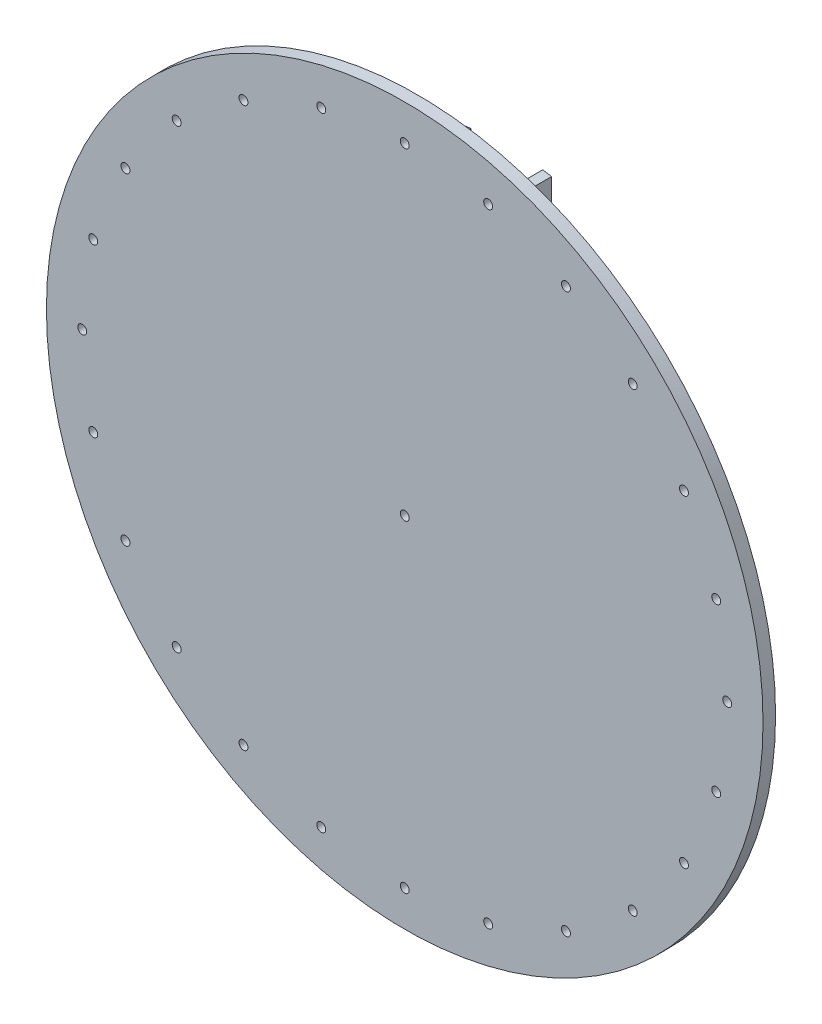
SolidWorks part; units mm, degrees
material "Plain Carbon Steel"
ref_plane "Front Plane" through (0, 0, 0) normal (0, 0, 1) x (1, 0, 0)
ref_plane "Top Plane" through (0, 0, 0) normal (0, 1, 0) x (1, 0, 0)
ref_plane "Right Plane" through (0, 0, 0) normal (1, 0, 0) x (0, 0, -1)
sketch "Sketch2" plane through (0, 0, 0) normal (0, 0, 1) x (1, 0, 0)
  line L0 (0, -23.094) -> (118.7439, -91.6509)
  line L1 (0, 28.8675) -> (142.4038, -53.3494) construction
  line L2 (20, 11.547) -> (138.7439, -57.0098)
  line L3 (-20, 11.547) -> (-20, 148.6607)
  line L4 (0, 23.094) -> (139.9038, -57.6795) construction
  line L5 (20, 11.547) -> (20, 148.6607)
  line L6 (0, -23.094) -> (-118.7439, -91.6509)
  line L7 (-20, -11.547) -> (119.9038, -92.3205) construction
  line L8 (-20, 11.547) -> (-138.7439, -57.0098)
  line L9 (-25, -14.4338) -> (117.4038, -96.6506) construction
  line L10 (-25, -14.4338) -> (-25, 150) construction
  line L11 (-25, 14.4338) -> (-25, 147.902)
  line L12 (0, -28.8675) -> (115.5869, -95.6016)
  line L13 (0, -28.8675) -> (-115.5869, -95.6016)
  line L14 (25, 14.4338) -> (25, 147.902)
  line L15 (-25, 14.4338) -> (-140.5869, -52.3004)
  line L16 (25, 14.4338) -> (140.5869, -52.3004)
  line L17 (-20, -11.547) -> (-20, 150) construction
  line L18 (20, -11.547) -> (20, 150) construction
  line L19 (25, -14.4338) -> (25, 150) construction
  line L20 (20, -11.547) -> (-119.9038, -92.3205) construction
  line L21 (25, -14.4338) -> (-117.4038, -96.6506) construction
  line L22 (0, 28.8675) -> (-142.4038, -53.3494) construction
  line L23 (0, 23.094) -> (-139.9038, -57.6795) construction
  arc A0 (25, 147.902) -> (20, 148.6607) centre (0, 0) ccw
  arc A1 (-140.5869, -52.3004) -> (-138.7439, -57.0098) centre (0, 0) ccw
  arc A2 (115.5869, -95.6016) -> (118.7439, -91.6509) centre (0, 0) ccw
  arc A3 (-118.7439, -91.6509) -> (-115.5869, -95.6016) centre (0, 0) ccw
  arc A4 (138.7439, -57.0098) -> (140.5869, -52.3004) centre (0, 0) ccw
  arc A5 (-20, 148.6607) -> (-25, 147.902) centre (0, 0) ccw
  point P20 (0, 0)
  dimension "D1" = 300
  dimension "D5" = 5
  dimension "D6" = 5
  dimension "D4" = 3
extrude "Boss-Extrude2" add sketch "Sketch2" along normal blind 50
sketch "Sketch3" plane through (0, 0, 50) normal (0, 0, 1) x (1, 0, 0)
  circle A0 centre (0, 0) radius 200
  dimension "D1" = 400
extrude "Boss-Extrude3" add sketch "Sketch3" along normal blind 7
sketch "Sketch4" plane through (0, 0, 0) normal (1, 0, 0) x (0, 0, -1)
  line L1 (0, 0) -> (216.2912, 0) construction
  circle A1 centre (-25, 40) radius 2.5
  circle A2 centre (-25, 70) radius 2.5
  circle A3 centre (-25, 100) radius 2.5
  circle A4 centre (-25, 130) radius 2.5
  dimension "D1" = 25
  dimension "D2" = 4
  dimension "25" = 40
extrude "Cut-Extrude1" cut sketch "Sketch4" against normal blind 170 and the other way blind 170
pattern_circular "CirPattern1" count 3 every 120 about axis through (0, 0, 50) along (0, 0, 1) of "Cut-Extrude1"
sketch "Sketch5" plane through (0, 0, 57) normal (0, 0, 1) x (1, 0, 0)
  circle A0 centre (0, 0) radius 2.5
  circle A1 centre (180, 0) radius 2.5
  dimension "D1" = 5
  dimension "D2" = 5
  dimension "D3" = 180
extrude "Cut-Extrude2" cut sketch "Sketch5" against normal blind 170
pattern_circular "CirPattern2" count 24 every 15 about axis through (0, 0, 0) along (0, 0, 1) of "Cut-Extrude2"
